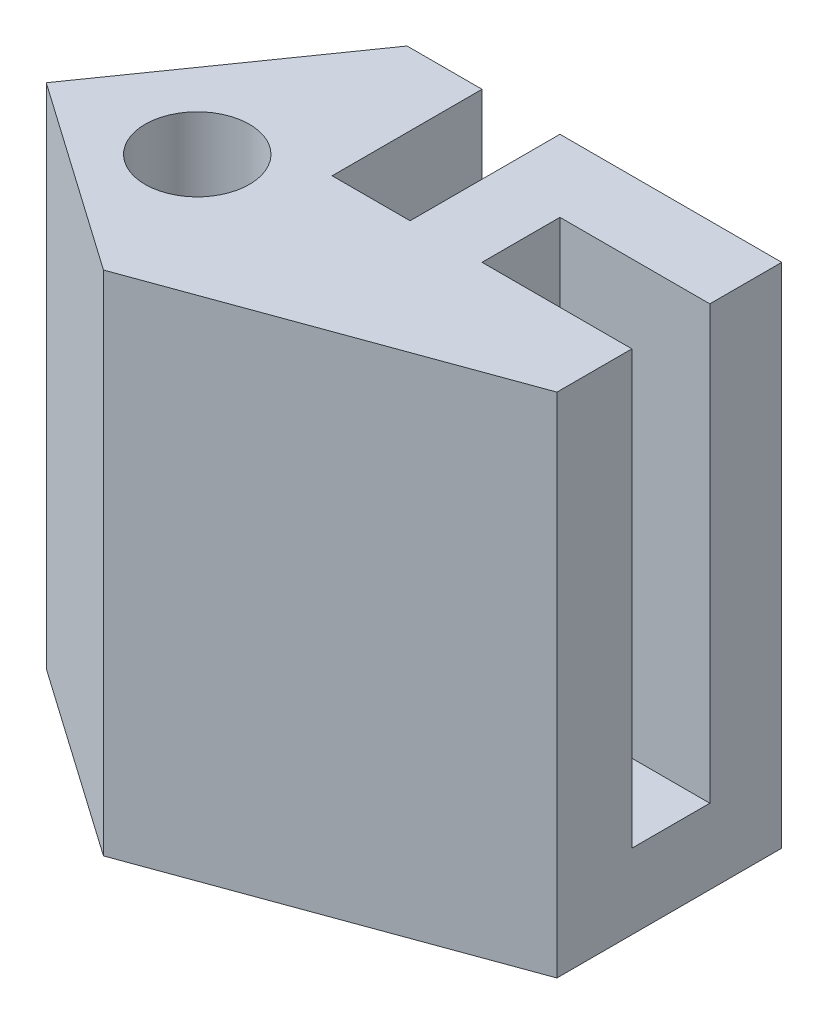
SolidWorks part; units mm, degrees
ref_plane "Front Plane" through (0, 0, 0) normal (0, 0, 1) x (1, 0, 0)
ref_plane "Top Plane" through (0, 0, 0) normal (0, 1, 0) x (1, 0, 0)
ref_plane "Right Plane" through (0, 0, 0) normal (1, 0, 0) x (0, 0, -1)
sketch "Sketch1" plane through (0, 0, 0) normal (0, 1, 0) x (1, 0, 0)
  line L0 (12.954, 19.05) -> (31.75, 19.05)
  line L1 (0, 0) -> (31.75, 0) construction
  line L8 (0, 0) -> (0, 19.05) construction
  line L12 (0, 19.05) -> (6.35, 19.05)
  line L13 (31.75, 0) -> (31.75, 6.35)
  line L15 (6.35, 19.05) -> (6.35, 6.35)
  line L16 (6.35, 6.35) -> (12.954, 6.35)
  line L24 (12.954, 19.05) -> (12.954, 6.35)
  line L25 (31.75, 6.35) -> (19.05, 6.35)
  line L27 (31.75, 12.954) -> (19.05, 12.954)
  line L28 (19.05, 6.35) -> (19.05, 12.954)
  line L29 (31.75, 12.954) -> (31.75, 19.05)
  line L30 (0, 19.05) -> (-12.5928, 1.0656)
  line L31 (-12.5928, 1.0656) -> (3.5747, -10.255)
  line L32 (3.5747, -10.255) -> (31.75, 0)
  line L33 (0, 0) -> (-3.6422, -5.2016) construction
  dimension "D1" = 12.7
  dimension "D2" = 6.604
  dimension "D3" = 6.35
  dimension "D4" = 6.096
  dimension "D5" = 35
  dimension "D6" = 20
  dimension "D7" = 6.35
  dimension "D8" = 6.096
extrude "Boss-Extrude1" add sketch "Sketch1" along normal blind 36.65
sketch "Sketch7" plane through (0, 36.65, 0) normal (0, 1, 0) x (1, 0, 0)
  line L0 (6.35, 19.05) -> (12.954, 19.05)
  line L1 (31.75, 6.35) -> (31.75, 12.954)
  line L13 (31.75, 12.954) -> (31.75, 19.05)
  line L14 (31.75, 19.05) -> (12.954, 19.05)
  line L15 (12.954, 19.05) -> (12.954, 6.35)
  line L16 (12.954, 6.35) -> (6.35, 6.35)
  line L17 (6.35, 6.35) -> (6.35, 19.05)
  line L18 (6.35, 19.05) -> (0, 19.05)
  line L19 (0, 19.05) -> (-12.5928, 1.0656)
  line L20 (-12.5928, 1.0656) -> (3.5747, -10.255)
  line L21 (3.5747, -10.255) -> (31.75, 0)
  line L22 (31.75, 0) -> (31.75, 6.35)
  line L23 (31.75, 6.35) -> (19.05, 6.35)
  line L24 (19.05, 6.35) -> (19.05, 12.954)
  line L25 (19.05, 12.954) -> (31.75, 12.954)
  line L26 (31.75, 12.954) -> (31.75, 19.05)
  line L27 (31.75, 19.05) -> (12.954, 19.05)
  line L31 (6.35, 19.05) -> (0, 19.05)
  line L32 (0, 19.05) -> (-12.5928, 1.0656)
  line L33 (-12.5928, 1.0656) -> (3.5747, -10.255)
  line L34 (3.5747, -10.255) -> (31.75, 0)
  line L35 (31.75, 0) -> (31.75, 6.35)
  dimension "D1" = 0
extrude "Boss-Extrude2" [suppressed] add sketch "Sketch7" along normal blind 6.35
sketch "Sketch8" plane through (0, 0, 0) normal (0, -1, 0) x (1, 0, 0)
  line L0 (6.35, -19.05) -> (12.954, -19.05)
  line L1 (31.75, -6.35) -> (31.75, -12.954)
  line L13 (31.75, -19.05) -> (31.75, -12.954)
  line L14 (31.75, -12.954) -> (19.05, -12.954)
  line L15 (19.05, -12.954) -> (19.05, -6.35)
  line L16 (19.05, -6.35) -> (31.75, -6.35)
  line L17 (31.75, -6.35) -> (31.75, 0)
  line L18 (31.75, 0) -> (3.5747, 10.255)
  line L19 (3.5747, 10.255) -> (-12.5928, -1.0656)
  line L20 (-12.5928, -1.0656) -> (0, -19.05)
  line L21 (0, -19.05) -> (6.35, -19.05)
  line L22 (6.35, -19.05) -> (6.35, -6.35)
  line L23 (6.35, -6.35) -> (12.954, -6.35)
  line L24 (12.954, -6.35) -> (12.954, -19.05)
  line L25 (12.954, -19.05) -> (31.75, -19.05)
  line L26 (31.75, -19.05) -> (31.75, -12.954)
  line L30 (31.75, -6.35) -> (31.75, 0)
  line L31 (31.75, 0) -> (3.5747, 10.255)
  line L32 (3.5747, 10.255) -> (-12.5928, -1.0656)
  line L33 (-12.5928, -1.0656) -> (0, -19.05)
  line L34 (0, -19.05) -> (6.35, -19.05)
  line L38 (12.954, -19.05) -> (31.75, -19.05)
  dimension "D1" = 0
extrude "Boss-Extrude3" add sketch "Sketch8" along normal blind 6.35
hole_wizard "S (0.348) Diameter Hole1" positions "Sketch9" profile "Sketch10" hole size "S" standard "ANSI Inch" end condition through all
sketch "Sketch9" plane through (0, 36.65, 0) normal (0, 1, 0) x (1, 0, 0)
  line L0 (-12.5928, 1.0656) -> (3.5747, -10.255) construction
  line L1 (0, 19.05) -> (-12.5928, 1.0656) construction
  point P4 (-0.9399, 2.2085)
  dimension "D1" = 7.62
  dimension "D2" = 8.89
sketch "Sketch10" plane through (-0.9399, 36.65, -2.2085) normal (1, 0, 0) x (0, 0, 1)
  line L0 (0, 0) -> (0, 43)
  line L1 (0, 43) -> (4.4196, 43)
  line L2 (4.4196, 43) -> (4.4196, 0)
  line L5 (4.4196, 0) -> (0, 0)
  line L11 (0, -6.35) -> (0, 107.95) construction
  dimension "Thru Hole Dia." = 8.8392
  dimension "Thru Hole Depth" = 43
hole_wizard "1/4 Clearance Hole2" [suppressed] positions "Sketch13" profile "Sketch12" hole size "1/4" standard "ANSI Inch"
sketch "Sketch13" plane through (0, 43, 0) normal (0, 1, 0) x (1, 0, 0)
  line L0 (-12.5928, 1.0656) -> (3.5747, -10.255) construction
  line L1 (0, 19.05) -> (-12.5928, 1.0656) construction
  point P0 (-0.9399, 2.2085)
  dimension "D1" = 7.62
  dimension "D2" = 8.89
sketch "Sketch12" plane through (-0.9399, 43, -2.2085) normal (1, 0, 0) x (0, 0, 1)
  line L0 (0, 0) -> (0, 43)
  line L1 (0, 43) -> (3.5712, 43)
  line L2 (3.5712, 43) -> (3.5712, 0)
  line L5 (3.5712, 0) -> (0, 0)
  line L11 (0, -6.35) -> (0, 107.95) construction
  dimension "Thru Hole Dia." = 7.1425
  dimension "Thru Hole Depth" = 43
equation "\"Material_thickness\"= 0.25in"
equation "\"Tollerence\"= 0.01in"
equation "\"Height\"= \"box_height\" - 0.25in"
equation "\"D1@Boss-Extrude1\"=\"Height\""
equation "\"box_width\" = 305mm"
equation "\"box_other_width\" = 170mm"
equation "\"box_height\" = 43mm"
